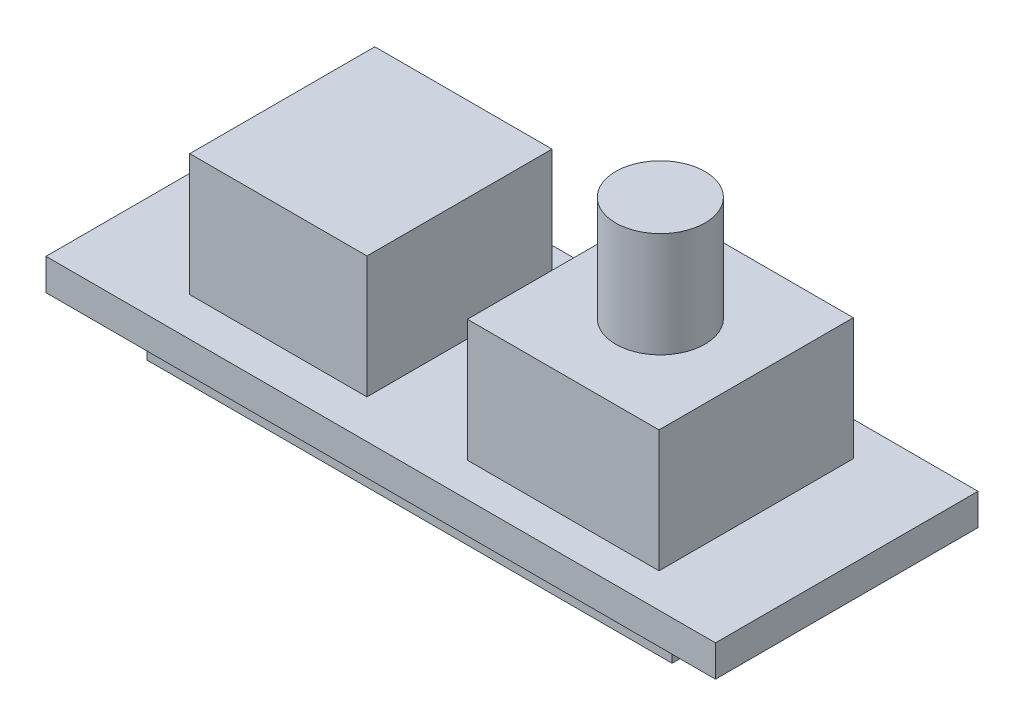
SolidWorks part; units mm, degrees
ref_plane "Front Plane" through (0, 0, 0) normal (0, 0, 1) x (1, 0, 0)
ref_plane "Top Plane" through (0, 0, 0) normal (0, 1, 0) x (1, 0, 0)
ref_plane "Right Plane" through (0, 0, 0) normal (1, 0, 0) x (0, 0, -1)
sketch "Sketch2" plane through (0, 0, 0) normal (0, 1, 0) x (1, 0, 0)
  line L1 (-12.75, 5) -> (12.75, 5)
  line L2 (-12.75, 5) -> (-12.75, -5)
  line L3 (-12.75, -5) -> (12.75, -5)
  line L4 (12.75, 5) -> (12.75, -5)
  line L5 (-12.75, 5) -> (12.75, -5) construction
  line L6 (-12.75, -5) -> (12.75, 5) construction
  point P0 (0, 0)
  dimension "D1" = 25.5
  dimension "D2" = 10
extrude "Boss-Extrude1" add sketch "Sketch2" along normal blind 1.2
sketch "Sketch4" plane through (0, 1.2, 0) normal (0, 1, 0) x (1, 0, 0)
  line L0 (0, 0) -> (-12.75, 0) construction
  line L1 (-12.75, 5) -> (-12.75, -5) construction
  line L2 (0, 0) -> (12.75, 0) construction
  line L3 (12.75, -5) -> (12.75, 5) construction
  line L4 (-2, 0) -> (2, 0) construction
  line L5 (-8.75, 3.525) -> (-2, 3.525)
  line L6 (-8.75, 3.525) -> (-8.75, -3.525)
  line L7 (-8.75, -3.525) -> (-2, -3.525)
  line L8 (-2, 3.525) -> (-2, -3.525)
  line L9 (-8.75, 3.525) -> (-2, -3.525) construction
  line L10 (-8.75, -3.525) -> (-2, 3.525) construction
  line L11 (2, 3.7) -> (9.3, 3.7)
  line L12 (2, 3.7) -> (2, -3.7)
  line L13 (2, -3.7) -> (9.3, -3.7)
  line L14 (9.3, 3.7) -> (9.3, -3.7)
  line L15 (2, 3.7) -> (9.3, -3.7) construction
  line L16 (2, -3.7) -> (9.3, 3.7) construction
  line L17 (0, 5) -> (0, -5) construction
  line L18 (12.75, 5) -> (-12.75, 5) construction
  line L19 (-12.75, -5) -> (12.75, -5) construction
  line L20 (0, -3.525) -> (2, -3.525) construction
  line L21 (0, -3.525) -> (-2, -3.525) construction
  point P5 (-5.375, 0)
  point P13 (5.65, 0)
  dimension "D1" = 7.4
  dimension "D2" = 7.3
  dimension "D3" = 7.05
  dimension "D4" = 6.75
  dimension "D5" = 4
  dimension "D6" = 2
extrude "Boss-Extrude2" add sketch "Sketch4" along normal blind 4.65
sketch "Sketch5" plane through (0, 5.85, 0) normal (0, 1, 0) x (1, 0, 0)
  line L0 (9.3, 3.7) -> (2, -3.7) construction
  line L1 (9.3, -3.7) -> (2, 3.7) construction
  line L2 (2, 3.7) -> (5.65, 0) construction
  circle A0 centre (5.65, 0) radius 1.7
  dimension "D1" = 3.4
extrude "Boss-Extrude3" add sketch "Sketch5" along normal blind 4
sketch "Sketch6" plane through (0, 0, 0) normal (0, -1, 0) x (1, 0, 0)
  line L1 (-10, 3.9) -> (10, 3.9)
  line L2 (-10, 3.9) -> (-10, -3.9)
  line L3 (-10, -3.9) -> (10, -3.9)
  line L4 (10, 3.9) -> (10, -3.9)
  line L5 (-10, 3.9) -> (10, -3.9) construction
  line L6 (-10, -3.9) -> (10, 3.9) construction
  point P0 (0, 0)
  dimension "D1" = 7.8
  dimension "D2" = 20
extrude "Boss-Extrude4" add sketch "Sketch6" along normal blind 1.4
